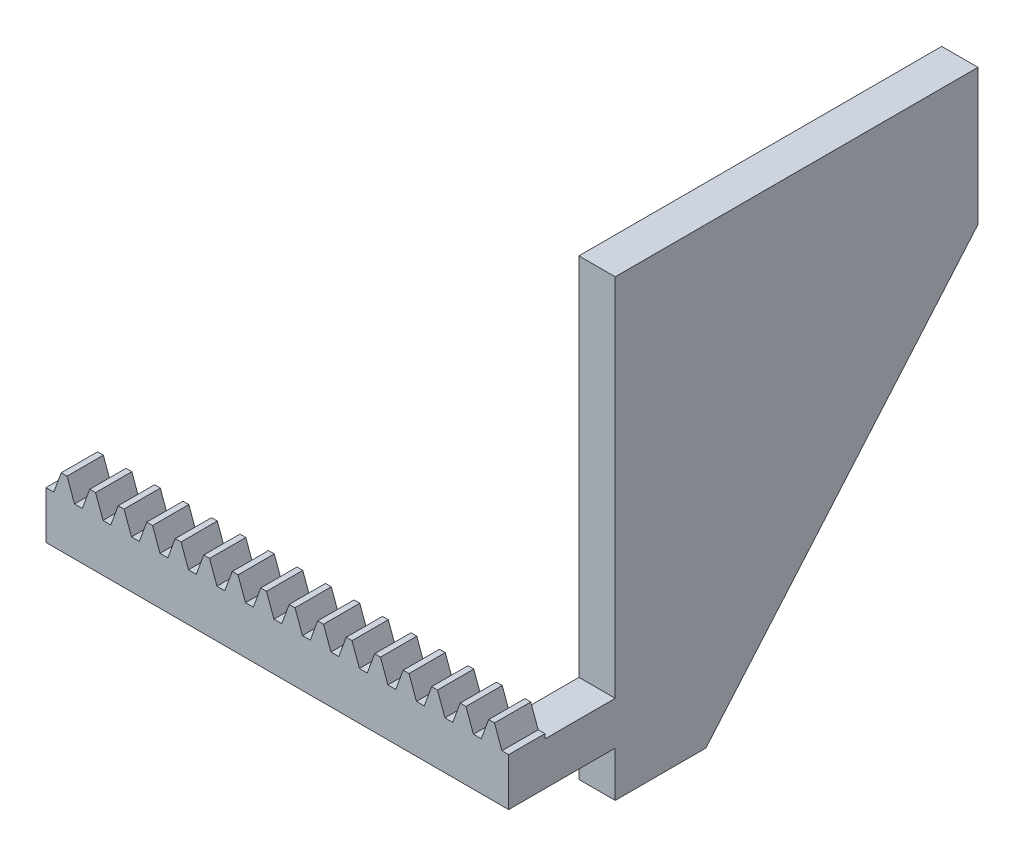
SolidWorks part; units mm, degrees
extrude "Blank" add sketch "BlankSke" against normal blind 8
sketch "BlankSke" plane through (0, 0, 0) normal (0, 0, 1) x (1, 0, 0)
  line L1 (0, 0) -> (120, 0)
  line L2 (0, 0) -> (0, 16)
  line L3 (0, 16) -> (120, 16)
  line L4 (120, 0) -> (120, 16)
  dimension "Length" = 120
  dimension "Blank_height" = 16
ref_plane "Plane1" through (0, 0, 0) normal (0, 0, 1) x (1, 0, 0)
ref_plane "Plane2" through (0, 0, 0) normal (0, 1, 0) x (1, 0, 0)
ref_plane "Plane3" through (0, 0, 0) normal (1, 0, 0) x (0, 0, -1)
sketch "HoldingSke" plane through (0, 0, 0) normal (0, 1, 0) x (1, 0, 0)
  line L0 (0, 0) -> (0.0696, 0.4951)
  line L1 (-15, 0) -> (100, 0) construction
  line L2 (0, 0) -> (-2.1039, 2.3779)
  line L3 (0, 0) -> (-11.863, 4.5341)
  line L4 (0, 0) -> (8.0624, 3.0949)
  line L5 (0, 0) -> (-23.7986, -8.8762)
  line L6 (0, 0) -> (-10.5278, -7.1032)
  line L9 (-71.009, 38.7566) -> (41.7541, 79.799)
  line L10 (-76.2, 4.3779) -> (-62.2, 4.3779)
  line L11 (0, 0) -> (-8, 0)
  line L12 (-76.2, 101.6) -> (-76.133, 101.6)
  line L13 (24.9733, 27.94) -> (52.9518, 28.4284)
  line L14 (24.9733, 27.94) -> (24.9743, 27.94)
  line L15 (24.9733, 27.94) -> (100.4006, 29.5858)
  circle A0 centre (0, 0) radius 19.05
  circle A1 centre (0, 0) radius 7
  circle A2 centre (0, 0) radius 12.7
  dimension "MPH" = 14
  dimension "Diameter" = 38.1
  dimension "Num_teeth" = 21
  dimension "Pitch" = 0.5
  dimension "Show_teeth" = 998
  dimension "Thickness" = 12.7
  dimension "Ap" = 20
  dimension "Pitch_height" = 14
  dimension "Width" = 8
  dimension "Backlash" = 0.067
  dimension "Addendum_fac" = 1
  dimension "Dedendum_fac" = 1.25
  dimension "Clearance_fac" = 0.25
  dimension "Dedendum_add" = 0.001
  dimension "Length" = 120
  dimension "Module" = 2
sketch "TooCutSkeIll" plane through (0, 0, 0) normal (0, 0, 1) x (1, 0, 0)
  line L0 (-2.4806, 15.9474) -> (-0.9819, 11.8296)
  line L1 (-0.5111, 11.5) -> (0.5111, 11.5)
  line L2 (0.9819, 11.8296) -> (2.4806, 15.9474)
  line L3 (120, 16) -> (0, 16) construction
  line L4 (0, 0) -> (0, 64.897) construction
  line L5 (-13.208, 14) -> (12.954, 14) construction
  line L6 (0, 0) -> (120, 0) construction
  line L7 (1.7718, 14) -> (1.7718, 48.7463) construction
  line L8 (-1.7718, 14) -> (-1.7718, 48.7463) construction
  line L9 (2.5558, 16) -> (2.5558, 16.0254)
  line L10 (-2.5558, 16) -> (-2.5558, 16.0254)
  line L11 (-2.5558, 16.0254) -> (2.5558, 16.0254)
  arc A0 (0.5111, 11.5) -> (0.9819, 11.8296) centre (0.5111, 12.001) ccw
  arc A1 (-0.9819, 11.8296) -> (-0.5111, 11.5) centre (-0.5111, 12.001) ccw
  arc A2 (2.5558, 16) -> (2.4806, 15.9474) centre (2.5558, 15.92) ccw
  arc A3 (-2.4806, 15.9474) -> (-2.5558, 16) centre (-2.5558, 15.92) ccw
  dimension "Pitch_height" = 14
  dimension "Addendum_plus" = 2.0254
  dimension "Pressure_angle" = 20
  dimension "Gap_width" = 3.5436
  dimension "Dedendum" = 2.5
extrude "ToothCutIll" [suppressed] cut sketch "TooCutSkeIll" against normal through all
sketch "TooCutSkeSim" plane through (0, 0, 0) normal (0, 0, 1) x (1, 0, 0)
  line L0 (0.8619, 11.5) -> (-0.8619, 11.5)
  line L1 (2.509, 16.0254) -> (0.8619, 11.5)
  line L2 (0, 17.4625) -> (0, 53.467) construction
  line L3 (2.509, 16.0254) -> (-2.509, 16.0254)
  line L6 (-2.509, 16.0254) -> (-0.8619, 11.5)
  line L9 (-1.7718, 14) -> (1.7718, 14) construction
  line L10 (0, 0) -> (120, 0) construction
  line L11 (1.7718, 14) -> (1.7718, 53.467) construction
  line L12 (-1.7718, 14) -> (-1.7718, 53.467) construction
  dimension "Pitch_height" = 14
  dimension "Addendum_plus" = 2.0254
  dimension "Pressure_angle" = 20
  dimension "Gap_width" = 3.5436
  dimension "Dedendum" = 2.5
extrude "ToothCutSim" cut sketch "TooCutSkeSim" against normal through all
pattern_linear "TeethCuts" count 20 spacing 6.2832 along (1, 0, 0) of "ToothCutIll", "ToothCutSim"
sketch "Sketch1" plane through (120, 0, 0) normal (1, 0, 0) x (0, 0, -1)
  line L0 (0, 1) -> (8, 1)
  line L1 (0, 0) -> (0, 11.5) construction
  line L2 (8, 0) -> (8, 11.5) construction
  line L3 (8, 1) -> (8, 0)
  line L4 (8, 0) -> (0, 0)
  line L5 (0, 0) -> (0, 1)
  dimension "D1" = 1
extrude "Cut-Extrude1" cut sketch "Sketch1" against normal through all
sketch "Sketch2" plane through (120, 0, 0) normal (1, 0, 0) x (0, 0, -1)
  line L0 (8, 1) -> (23.5, 1)
  line L1 (23.5, 1) -> (23.5, -9)
  line L3 (103.5, 61) -> (103.5, 91)
  line L5 (23.5, 91) -> (23.5, 10.5)
  line L6 (23.5, 10.5) -> (8, 10.5)
  line L7 (8, 1) -> (8, 11.5) construction
  line L8 (8, 10.5) -> (8, 1)
  line L9 (23.5, -9) -> (43.5, -9)
  line L10 (43.5, -9) -> (103.5, 61)
  line L13 (23.5, 91) -> (103.5, 91)
  dimension "D1" = 9.5
  dimension "D2" = 20
  dimension "D3" = 30
  dimension "D4" = 100
  dimension "D5" = 10
  dimension "D6" = 15.5
  dimension "D7" = 80
extrude "Boss-Extrude2" add sketch "Sketch2" against normal blind 8
sketch "Sketch3" plane through (0, 0, 0) normal (0, 0, 1) x (1, 0, 0)
  line L0 (0, 1) -> (0, 11.5)
  line L1 (0, 11.5) -> (0, 1) construction
  line L2 (0.8619, 11.5) -> (2.4997, 16)
  line L3 (2.4997, 16) -> (3.7834, 16)
  line L4 (3.7834, 16) -> (5.4213, 11.5)
  line L6 (5.4213, 11.5) -> (7.1451, 11.5) construction
  line L8 (0, 1) -> (120, 1) construction
  line L9 (6.1613, 1) -> (0, 1)
  line L10 (5.4213, 11.5) -> (7.1451, 11.5)
  line L11 (7.1451, 11.5) -> (8.7829, 16)
  line L12 (8.7829, 16) -> (10.0666, 16)
  line L13 (10.0666, 16) -> (11.7045, 11.5)
  line L14 (11.7045, 11.5) -> (13.4282, 11.5)
  line L15 (13.4282, 11.5) -> (15.0661, 16)
  line L16 (15.0661, 16) -> (15.708, 16)
  line L17 (16.3498, 16) -> (15.0661, 16) construction
  line L19 (0, 1) -> (112, 1) construction
  line L20 (15.708, 1) -> (6.1613, 1)
  line L21 (15.708, 16) -> (16.3498, 16)
  line L22 (16.3498, 16) -> (17.9877, 11.5)
  line L24 (17.9877, 11.5) -> (17.9877, 1)
  line L26 (17.9877, 1) -> (15.708, 1)
  arc A0 (0, 11.5) -> (0.8619, 11.5) centre (0.4309, 11.5) cw
extrude "Cut-Extrude2" cut sketch "Sketch3" against normal through all
equation "' \"Module@HoldingSke\" = 6.35"
equation "' \"Num_teeth@HoldingSke\" = 12"
equation "' \"Ap@HoldingSke\" =  20"
equation "' \"Ap@HoldingSke\" = 20"
equation "' \"Width@HoldingSke\" = 0.25 * 25.4"
equation "' \"Show_teeth@HoldingSke\" = 500"
equation "' \"Backlash@HoldingSke\" = 0.009 * 25.4"
equation "' \"Addendum_fac@HoldingSke\" = 1.0"
equation "' \"Dedendum_fac@HoldingSke\" = 1.25"
equation "' \"Dedendum_add@HoldingSke\" = 0.00005 * 25.4"
equation "' \"Clearance_fac@HoldingSke\" = 0.25"
equation "' \"Pitch_height@HoldingSke\" = 1 * 25.4"
equation "' \"Length@HoldingSke\" = 4.71 * 25.4"
equation "\"Pitch@HoldingSke\" = 1 / \"Module@HoldingSke\""
equation "\"MPH@HoldingSke\" = \"Dedendum_fac@HoldingSke\" / \"Pitch@HoldingSke\" + 2 * \"Dedendum_add@HoldingSke\" + 0.002 * 25.4"
equation "\"MPH@HoldingSke\" = ((sgn( \"MPH@HoldingSke\" - \"Pitch_height@HoldingSke\")+1)*( \"MPH@HoldingSke\" - \"Pitch_height@HoldingSke\"))/2 + \"Pitch_height@HoldingSke\""
equation "\"Blank_height@BlankSke\" = \"Pitch_height@HoldingSke\" + \"Addendum_fac@HoldingSke\"  / \"Pitch@HoldingSke\" "
equation "\"Length@BlankSke\" =  \"Length@HoldingSke\""
equation "\"Face_width@Blank\" = \"Width@HoldingSke\""
equation "\"Pressure_angle@TooCutSkeIll\" = \"Ap@HoldingSke\""
equation "\"Addendum_plus@TooCutSkeIll\" =  \"Addendum_fac@HoldingSke\"  / \"Pitch@HoldingSke\" + 0.001 *25.4"
equation "\"Dedendum@TooCutSkeIll\" = \"Dedendum_fac@HoldingSke\"  / \"Pitch@HoldingSke\""
equation "\"Pitch_height@TooCutSkeIll\" =  \"MPH@HoldingSke\""
equation "\"Gap_width@TooCutSkeIll\" = 3.14159265 / 2 / \"Pitch@HoldingSke\" + 6 * \"Backlash@HoldingSke\""
equation "\"Pressure_angle@TooCutSkeSim\" = \"Ap@HoldingSke\""
equation "\"Addendum_plus@TooCutSkeSim\" =  \"Addendum_fac@HoldingSke\"  / \"Pitch@HoldingSke\" + 0.001 * 25.4"
equation "\"Dedendum@TooCutSkeSim\" = \"Dedendum_fac@HoldingSke\"  / \"Pitch@HoldingSke\""
equation "\"Pitch_height@TooCutSkeSim\" =  \"MPH@HoldingSke\""
equation "\"Gap_width@TooCutSkeSim\" = 3.14159265 / 2 / \"Pitch@HoldingSke\" + 6 * \"Backlash@HoldingSke\""
equation "\"Root_fillet@TooCutSkeIll\" = \"Clearance_fac@HoldingSke\" / \"Pitch@HoldingSke\" + \"Dedendum_add@HoldingSke\""
equation "\"Break_rad@TooCutSkeIll\" = 0.02 / \"Pitch@HoldingSke\" * 2"
equation "\"Linear_pitch@TeethCuts\" = 3.14159265 / \"Pitch@HoldingSke\""
equation "\"Num_teeth@HoldingSke\" = int( ( \"Length@HoldingSke\" + 0 ) / (3.14159265 / \"Pitch@HoldingSke\")) + 0.9999  + 1"
equation " \"Num_teeth@TeethCuts\" = int( \"Show_teeth@HoldingSke\" ) + 1"
equation " \"Num_teeth@TeethCuts\" = ((sgn( \"Num_teeth@TeethCuts\" - \"Num_teeth@HoldingSke\" )-1)*( \"Num_teeth@TeethCuts\" - \"Num_teeth@HoldingSke\" ))/-2+ \"Num_teeth@HoldingSke\""
equation " \"Num_teeth@TeethCuts\" = ((sgn( \"Num_teeth@TeethCuts\" - 2.0)+1)*( \"Num_teeth@TeethCuts\" - 2.0))/2 +2.0"
